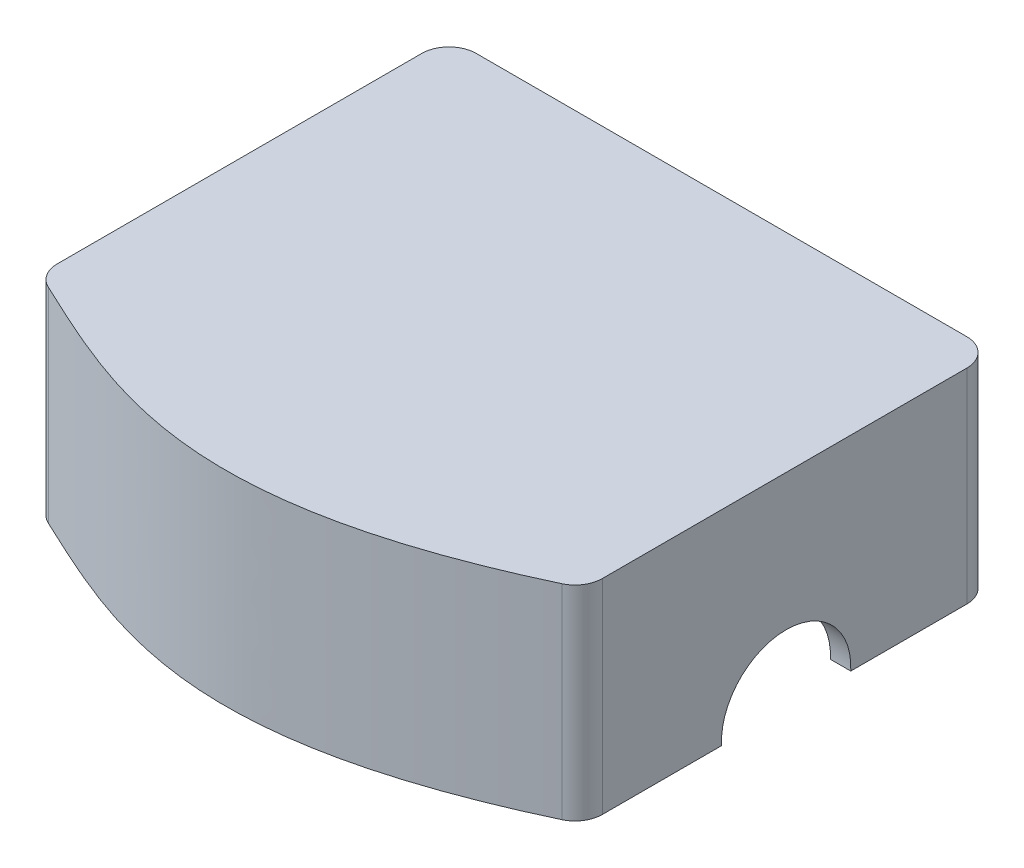
SolidWorks part; units mm, degrees
ref_plane "Front Plane" through (0, 0, 0) normal (0, 0, 1) x (1, 0, 0)
ref_plane "Top Plane" through (0, 0, 0) normal (0, 1, 0) x (1, 0, 0)
ref_plane "Right Plane" through (0, 0, 0) normal (1, 0, 0) x (0, 0, -1)
sketch "Sketch1" plane through (0, 0, 0) normal (0, 1, 0) x (1, 0, 0)
  line L0 (-188.5267, -155.5721) -> (-94.2634, -200) construction
  line L1 (-180, 150) -> (180, 150)
  line L2 (-200, 130) -> (-200, -137.4808)
  line L4 (200, 130) -> (200, -137.4808)
  line L5 (-200, 150) -> (200, -150) construction
  line L6 (-200, -150) -> (200, 150) construction
  line L7 (0, -244.4279) -> (188.5267, -155.5721) construction
  line L8 (-515.669, -250) -> (87.3072, -250) construction
  line L9 (-94.2634, -200) -> (0, -244.4279) construction
  arc A0 (188.5267, -155.5721) -> (200, -137.4808) centre (180, -137.4808) ccw
  arc A1 (-188.5267, -155.5721) -> (-200, -137.4808) centre (-180, -137.4808) cw
  arc A2 (180, 150) -> (200, 130) centre (180, 130) cw
  arc A3 (-180, 150) -> (-200, 130) centre (-180, 130) ccw
  spline S4 degree 3 poles (-188.5267, -155.5721) (-94.2634, -200) (0, -244.4279) (188.5267, -155.5721) knots 0 0 0 0 1 1 1 1
  point P0 (0, 0)
  dimension "D2" = 20
  dimension "D3" = 20
  dimension "D1" = 400
extrude "Boss-Extrude5" add sketch "Sketch1" along normal blind 150
sketch "Sketch7" plane through (0, 0, 0) normal (0, -1, 0) x (1, 0, 0)
  line L24 (-180, -135) -> (180, -135)
  line L25 (185, -130) -> (185, 137.4808)
  line L26 (-185, 137.4808) -> (-185, -130)
  line L27 (-180, -135) -> (180, -135)
  line L28 (185, -130) -> (185, 137.4808)
  line L29 (-185, 137.4808) -> (-185, -130)
  arc A29 (-185, -130) -> (-180, -135) centre (-180, -130) ccw
  arc A30 (180, -135) -> (185, -130) centre (180, -130) ccw
  arc A31 (185, 137.4808) -> (182.1317, 142.0036) centre (180, 137.4808) ccw
  arc A32 (-182.1317, 142.0036) -> (-185, 137.4808) centre (-180, 137.4808) ccw
  arc A33 (-185, -130) -> (-180, -135) centre (-180, -130) ccw
  arc A34 (180, -135) -> (185, -130) centre (180, -130) ccw
  arc A35 (185, 137.4808) -> (182.1317, 142.0036) centre (180, 137.4808) ccw
  arc A36 (-182.1317, 142.0036) -> (-185, 137.4808) centre (-180, 137.4808) ccw
  spline S11 degree 3 poles (2649.003, 2757.8417) (975.8779, -994.2668) (664.9409, -44.936) (123.8875, 166.5719) (109.0423, 171.733) (86.4514, 178.3598) (78.867, 180.382) (63.5743, 183.9991) (55.8661, 185.5939) (40.3071, 188.2916) (32.4563, 189.3945) (20.5568, 190.6231) (16.5697, 190.9616) (8.5513, 191.4858) (4.5442, 191.6699) (-7.4544, 191.9806) (-15.4302, 191.8655) (-31.3333, 190.9656) (-39.2606, 190.1805) (-51.1149, 188.4963) (-55.0602, 187.8506) (-60.9691, 186.7572) (-62.9373, 186.372) (-66.8706, 185.5603) (-68.8361, 185.1338) (-78.6181, 182.9092) (-86.3295, 180.8274) (-101.5592, 176.1528) (-109.0774, 173.56) (-123.9631, 167.9757) (-131.3306, 164.9843) (-428.8875, 37.7879) (-638.1695, -300.4161) (-2371.4422, 3392.3163) knots -4.357651 -4.357651 -4.357651 -4.357651 0.125 0.125 0.25 0.25 0.3125 0.3125 0.375 0.375 0.4375 0.4375 0.46875 0.46875 0.5 0.5 0.5625 0.5625 0.625 0.625 0.65625 0.65625 0.671875 0.671875 0.6875 0.6875 0.75 0.75 0.8125 0.8125 0.875 0.875 3.354469 3.354469 3.354469 3.354469 only from (182.1317, 142.0036) to (-182.1317, 142.0036)
  spline S12 degree 3 poles (182.1317, 142.0036) (167.7544, 148.7799) (153.2438, 155.096) (123.8875, 166.5719) (109.0423, 171.733) (86.4514, 178.3598) (78.867, 180.382) (63.5743, 183.9991) (55.8661, 185.5939) (40.3071, 188.2916) (32.4563, 189.3945) (20.5568, 190.6231) (16.5697, 190.9616) (8.5513, 191.4858) (4.5442, 191.6699) (-7.4544, 191.9806) (-15.4302, 191.8655) (-31.3333, 190.9656) (-39.2606, 190.1805) (-51.1149, 188.4963) (-55.0602, 187.8506) (-60.9691, 186.7572) (-62.9373, 186.372) (-66.8706, 185.5603) (-68.8361, 185.1338) (-78.6181, 182.9092) (-86.3295, 180.8274) (-101.5592, 176.1528) (-109.0774, 173.56) (-123.9631, 167.9757) (-131.3306, 164.9843) (-153.2789, 155.602) (-167.7054, 148.803) (-182.1317, 142.0036) knots 0 0 0 0 0.125 0.125 0.25 0.25 0.3125 0.3125 0.375 0.375 0.4375 0.4375 0.46875 0.46875 0.5 0.5 0.5625 0.5625 0.625 0.625 0.65625 0.65625 0.671875 0.671875 0.6875 0.6875 0.75 0.75 0.8125 0.8125 0.875 0.875 1 1 1 1
  dimension "D1" = 15
extrude "Cut-Extrude4" cut sketch "Sketch7" against normal blind 130
sketch "Sketch8" plane through (200, 0, 0) normal (1, 0, 0) x (0, 0, -1)
  circle A0 centre (-2.5747, 2.5) radius 47.5
  dimension "D2" = 95
  dimension "D1" = 2.5
extrude "Cut-Extrude5" cut sketch "Sketch8" against normal through all
